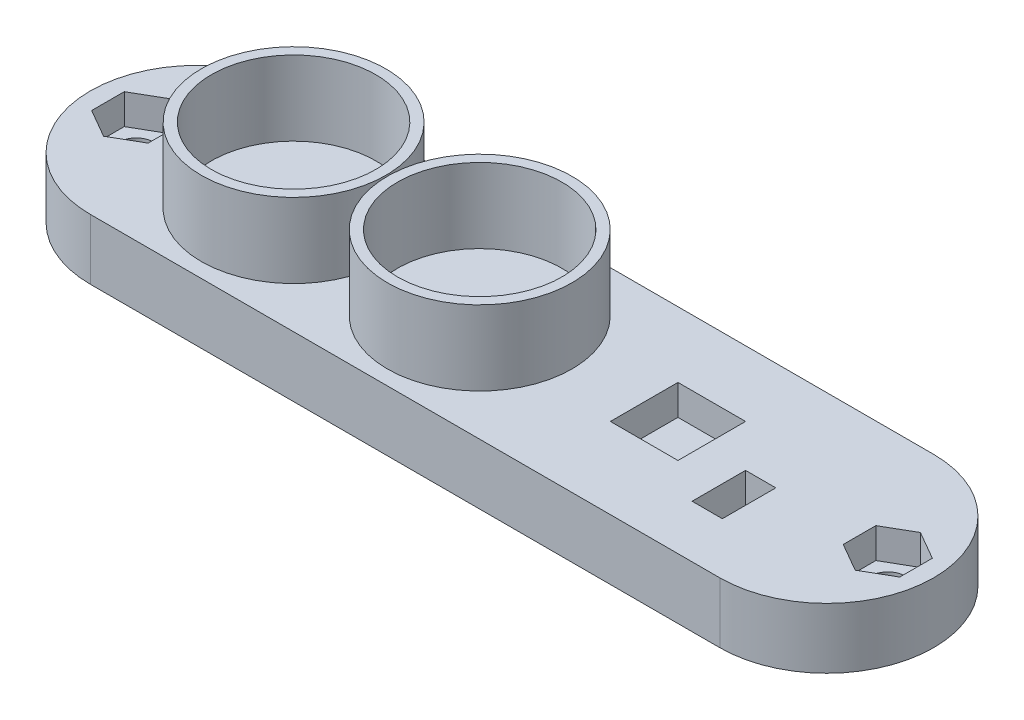
SolidWorks part; units mm, degrees
material "6061 Alloy"
ref_plane "Front Plane" through (0, 0, 0) normal (0, 0, 1) x (1, 0, 0)
ref_plane "Top Plane" through (0, 0, 0) normal (0, 1, 0) x (1, 0, 0)
ref_plane "Right Plane" through (0, 0, 0) normal (1, 0, 0) x (0, 0, -1)
sketch "Sketch1" plane through (0, 0, 0) normal (0, 1, 0) x (1, 0, 0)
  line L0 (-31.2, 0) -> (31.2, 0) construction
  line L2 (-31.2, 10.6) -> (31.2, 10.6)
  line L3 (-31.2, -10.6) -> (31.2, -10.6)
  arc A0 (-31.2, 10.6) -> (-31.2, -10.6) centre (-31.2, 0) ccw
  arc A1 (31.2, -10.6) -> (31.2, 10.6) centre (31.2, 0) ccw
  point P5 (0, 0)
  dimension "D1" = 62.4
  dimension "D2" = 21.2
extrude "Boss-Extrude1" add sketch "Sketch1" along normal blind 6
sketch "Sketch2" plane through (0, 6, 0) normal (0, 1, 0) x (1, 0, 0)
  circle A0 centre (-21.65, 0) radius 9.15
  circle A1 centre (-21.65, 0) radius 8.15
  arc A2 (-31.2, 10.6) -> (-31.2, -10.6) centre (-31.2, 0) ccw construction
  circle A3 centre (-3.2, 0) radius 9.15
  circle A4 centre (-3.2, 0) radius 8.15
  point P6 (-41.8, 0)
  dimension "D1" = 18.3
  dimension "D2" = 1
  dimension "D4" = 18.45
  dimension "D3" = 20.15
extrude "Boss-Extrude2" add sketch "Sketch2" along normal blind 7.4
sketch "Sketch3" plane through (0, 6, 0) normal (0, 1, 0) x (1, 0, 0)
  line L0 (0, -7.37) -> (0, 7.37) construction
  line L1 (-37.25, -3.2332) -> (-34.45, -1.6166)
  line L2 (-34.45, -1.6166) -> (-34.45, 1.6166)
  line L3 (-34.45, 1.6166) -> (-37.25, 3.2332)
  line L4 (-37.25, 3.2332) -> (-40.05, 1.6166)
  line L5 (-40.05, 1.6166) -> (-40.05, -1.6166)
  line L6 (-40.05, -1.6166) -> (-37.25, -3.2332)
  line L7 (37.25, -3.2332) -> (40.05, -1.6166)
  line L8 (40.05, -1.6166) -> (40.05, 1.6166)
  line L9 (40.05, 1.6166) -> (37.25, 3.2332)
  line L10 (37.25, 3.2332) -> (34.45, 1.6166)
  line L11 (34.45, 1.6166) -> (34.45, -1.6166)
  line L12 (34.45, -1.6166) -> (37.25, -3.2332)
  circle A0 centre (-37.25, 0) radius 2.8 construction
  circle A1 centre (37.25, 0) radius 2.8 construction
  dimension "D1" = 5.6
  dimension "D2" = 37.25
  dimension "D3" = 74.5
extrude "Cut-Extrude1" cut sketch "Sketch3" against normal blind 3
sketch "Sketch4" plane through (0, 3, 0) normal (0, 1, 0) x (1, 0, 0)
  circle A0 centre (-37.25, 0) radius 1.75
  circle A1 centre (37.25, 0) radius 1.75
  dimension "D1" = 3.5
  dimension "D2" = 37.25
  dimension "D3" = 74.5
extrude "Cut-Extrude2" cut sketch "Sketch4" against normal through all
sketch "Sketch5" plane through (0, 6, 0) normal (0, 1, 0) x (1, 0, 0)
  line L0 (31.2, 10.6) -> (-31.2, 10.6) construction
  line L1 (23.25, -0.1) -> (26.25, -0.1)
  line L2 (23.25, -0.1) -> (23.25, -5.4)
  line L3 (23.25, -5.4) -> (26.25, -5.4)
  line L4 (26.25, -0.1) -> (26.25, -5.4)
  line L6 (12.35, 4.1) -> (19.05, 4.1)
  line L7 (12.35, 4.1) -> (12.35, -2.6)
  line L8 (12.35, -2.6) -> (19.05, -2.6)
  line L9 (19.05, 4.1) -> (19.05, -2.6)
  circle A0 centre (37.25, 0) radius 1.75 construction
  dimension "D1" = 5.3
  dimension "D2" = 3
  dimension "D3" = 10.7
  dimension "D4" = 6.7
  dimension "D5" = 4.2
  dimension "D6" = 6.5
  dimension "D7" = 18.2
extrude "Cut-Extrude3" cut sketch "Sketch5" against normal blind 3
